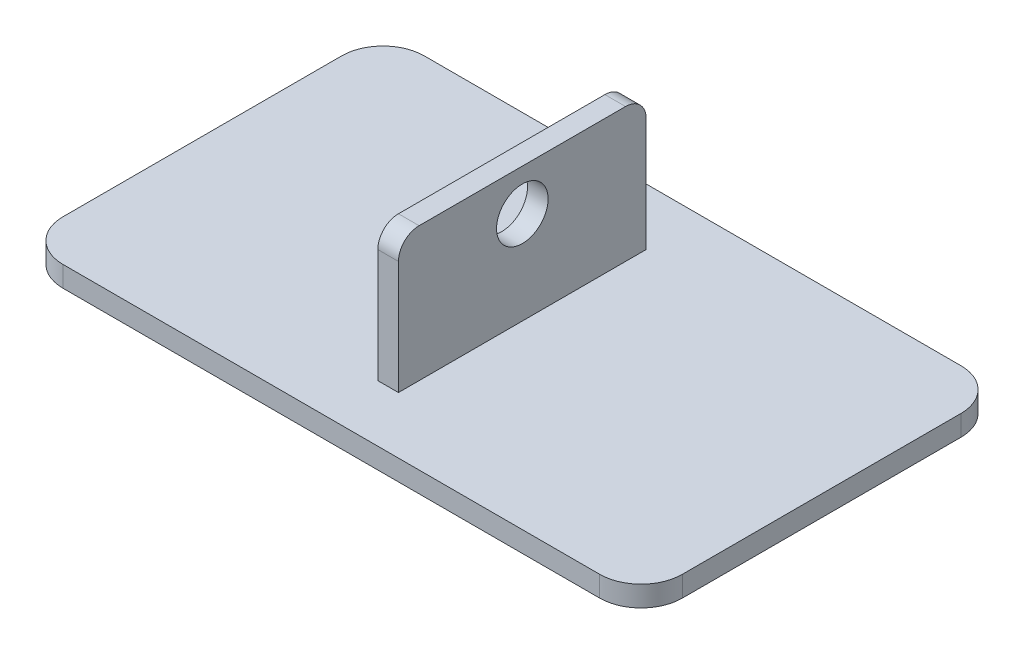
SolidWorks part; units mm, degrees
ref_plane "Front Plane" through (0, 0, 0) normal (0, 0, 1) x (1, 0, 0)
ref_plane "Top Plane" through (0, 0, 0) normal (0, 1, 0) x (1, 0, 0)
ref_plane "Right Plane" through (0, 0, 0) normal (1, 0, 0) x (0, 0, -1)
sketch "Sketch1" plane through (0, 0, 0) normal (0, 1, 0) x (1, 0, 0)
  line L1 (-150, 87.5) -> (150, 87.5)
  line L2 (-150, 87.5) -> (-150, -87.5)
  line L3 (-150, -87.5) -> (150, -87.5)
  line L4 (150, 87.5) -> (150, -87.5)
  line L5 (-150, 87.5) -> (150, -87.5) construction
  line L6 (-150, -87.5) -> (150, 87.5) construction
  point P0 (0, 0)
  dimension "D1" = 300
  dimension "D2" = 175
extrude "Boss-Extrude1" add sketch "Sketch1" along normal blind 10
sketch "Sketch2" plane through (0, 10, 0) normal (0, 1, 0) x (1, 0, 0)
  line L4 (5, -60) -> (5, 60)
  line L6 (-5, -60) -> (-5, 60)
  line L7 (-5, -60) -> (5, -60)
  line L11 (-5, 60) -> (5, 60)
  point P9 (0, 0)
  dimension "D2" = 120
extrude "Boss-Extrude2" add sketch "Sketch2" along normal blind 65
sketch "Sketch3" plane through (5, 0, 0) normal (1, 0, 0) x (0, 0, -1)
  line L0 (0, 42.5) -> (0, 55)
  line L2 (-12.5, 55) -> (12.5, 55) construction
  circle A0 centre (0, 55) radius 12.5
  dimension "D2" = 25
extrude "Cut-Extrude1" cut sketch "Sketch3" against normal blind 10 contours L2 L0 A0 | L2 A0 L0 | A0 L2
fillet "Fillet1" radius 10 2 edges at (0, 75, 60) (0, 75, -60)
fillet "Fillet2" radius 20 4 edges at (-150, 5, -87.5) (150, 5, -87.5) (150, 5, 87.5) (-150, 5, 87.5)
